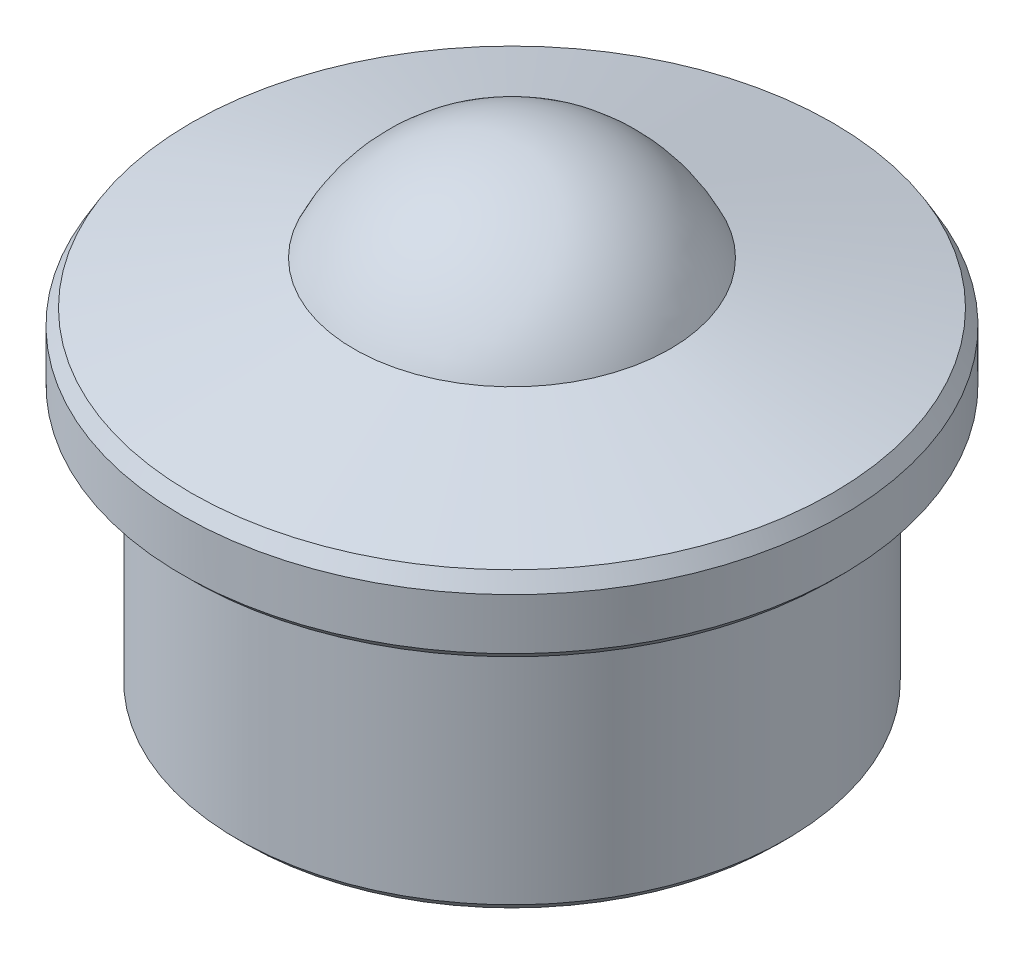
SolidWorks part; units mm, degrees
ref_plane "前视基准面" through (0, 0, 0) normal (0, 0, 1) x (1, 0, 0)
ref_plane "上视基准面" through (0, 0, 0) normal (0, 1, 0) x (1, 0, 0)
ref_plane "右视基准面" through (0, 0, 0) normal (1, 0, 0) x (0, 0, -1)
other "Configuration Table"
sketch "草图2" plane through (0, 0, 0) normal (0, 0, 1) x (1, 0, 0)
  line L0 (0, 0) -> (0, 26)
  line L1 (0, 0) -> (15, 0)
  line L2 (15, 0) -> (15, 14)
  line L3 (15, 14) -> (18, 14)
  line L4 (18, 14) -> (18, 18)
  line L5 (18, 18) -> (8.6328, 20.5)
  arc A0 (8.6328, 20.5) -> (0, 26) centre (0, 16.475) ccw
  dimension "D1" = 15
  dimension "D6" = 9.525
  dimension "D2" = 26
  dimension "D3" = 12
  dimension "D4" = 18
  dimension "D5" = 5.5
  dimension "D7" = 4
revolve "旋转1" add sketch "草图2" angle 360 about L0
chamfer "倒角1" distance 0.5 angle 45 3 edges at (0, 0, -15) (0, 14, -18) (0, 18, -18)
